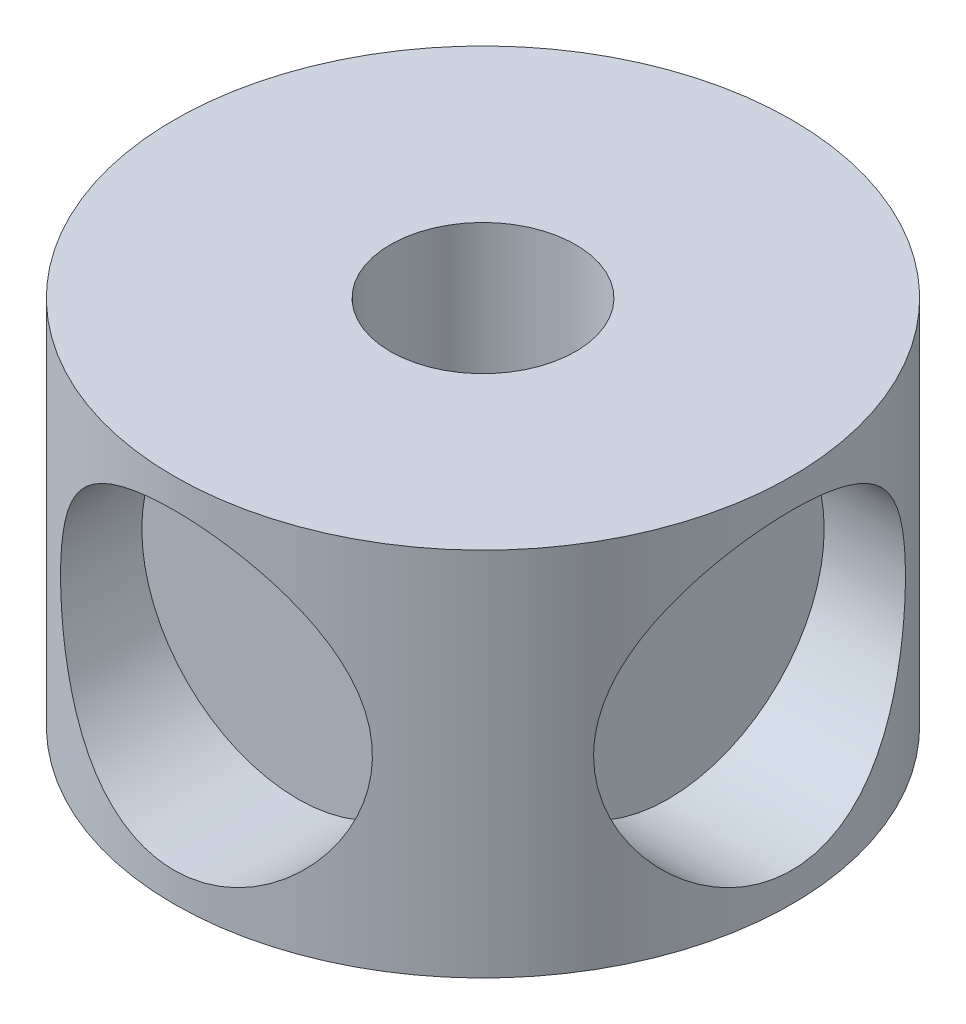
SolidWorks part; units mm, degrees
ref_plane "前视基准面" through (0, 0, 0) normal (0, 0, 1) x (1, 0, 0)
ref_plane "上视基准面" through (0, 0, 0) normal (0, 1, 0) x (1, 0, 0)
ref_plane "右视基准面" through (0, 0, 0) normal (1, 0, 0) x (0, 0, -1)
sketch "草图1" plane through (0, 0, 0) normal (0, 1, 0) x (1, 0, 0)
  circle A0 centre (0, 0) radius 10
  circle A1 centre (0, 0) radius 3
  dimension "D1" = 20
  dimension "D2" = 6
extrude "凸台-拉伸1" add sketch "草图1" along normal blind 12
sketch "草图2" plane through (0, 0, 0) normal (0, 0, 1) x (1, 0, 0)
  line L0 (0, 12.623) -> (0, 0) construction
  line L1 (-10, 6) -> (10, 6) construction
  line L2 (-10, 12) -> (-10, 0) construction
  line L3 (10, 0) -> (10, 12) construction
  circle A0 centre (0, 6) radius 5.05
  dimension "D1" = 10.1
extrude "切除-拉伸1" cut sketch "草图2" along normal blind 12 from offset 6
pattern_circular "阵列(圆周)1" count 4 every 90 about axis through (0, 0, 0) along (0, 1, 0) of "切除-拉伸1"
